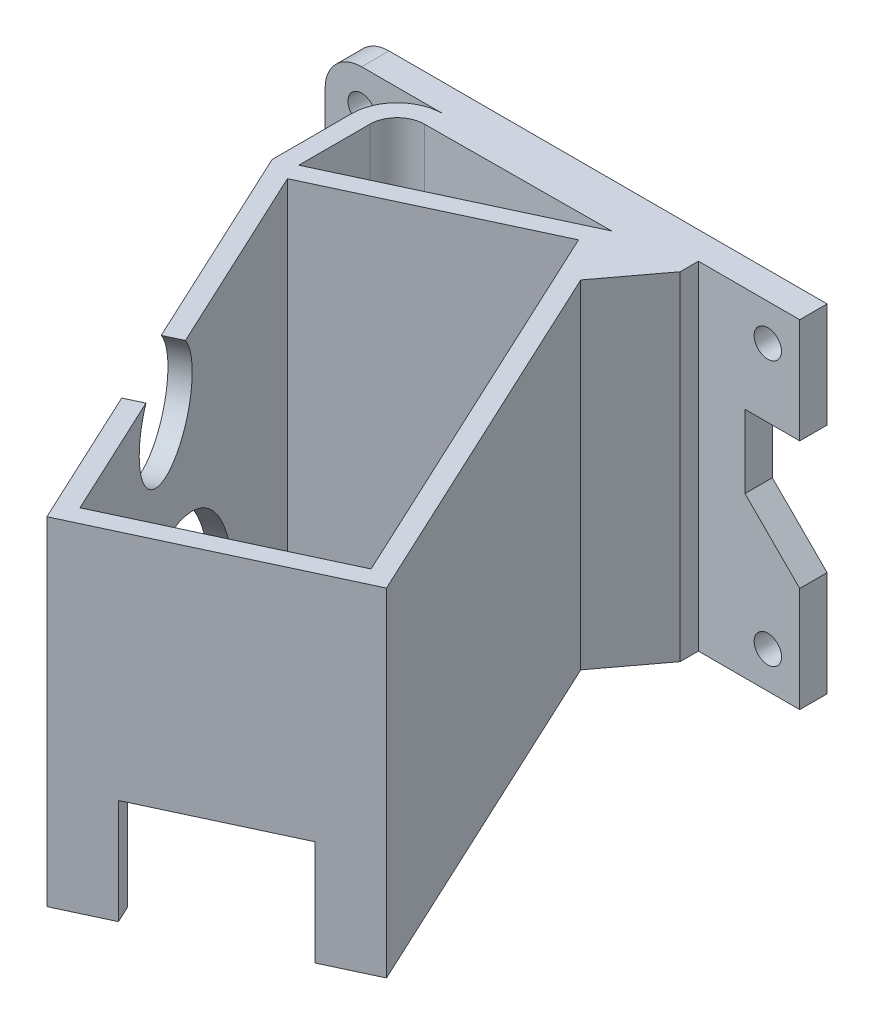
SolidWorks part; units mm, degrees
ref_plane "Alzado" through (0, 0, 0) normal (0, 0, 1) x (1, 0, 0)
ref_plane "Planta" through (0, 0, 0) normal (0, 1, 0) x (1, 0, 0)
ref_plane "Vista lateral" through (0, 0, 0) normal (1, 0, 0) x (0, 0, -1)
sketch "Croquis1" plane through (0, 0, 0) normal (0, 0, 1) x (1, 0, 0)
  line L0 (-56.1973, 4.9619) -> (-49.1973, 11.9619)
  line L1 (-52.1973, 33.4619) -> (-4.1973, 33.4619)
  line L2 (-56.1973, 29.4619) -> (-56.1973, 0.4619)
  line L3 (-52.4067, -3.5381) -> (-4.1973, -3.5381)
  line L4 (-4.1973, 33.4619) -> (-4.1973, -3.5381)
  line L5 (-56.1973, 24.9619) -> (-49.1973, 24.9619)
  line L6 (-56.1973, 24.9619) -> (-56.1973, 4.9619)
  line L7 (-56.1973, 4.9619) -> (-49.1973, 4.9619)
  line L8 (-4.1973, 7.9619) -> (-10.1973, 13.9619)
  line L9 (-4.1973, 21.9619) -> (-10.1973, 21.9619)
  line L10 (-4.1973, 21.9619) -> (-4.1973, 7.9619)
  line L11 (-4.1973, 7.9619) -> (-10.1973, 7.9619)
  line L13 (-49.1973, 11.9619) -> (-49.1973, 24.9619)
  line L14 (-10.1973, 13.9619) -> (-10.1973, 21.9619)
  circle A0 centre (-52.1973, 29.4619) radius 1.5
  circle A1 centre (-7.6973, 29.4619) radius 1.5
  circle A2 centre (-52.1915, 0.4619) radius 1.5
  circle A3 centre (-7.6915, 0.4619) radius 1.5
  arc A4 (-56.1973, 29.4619) -> (-52.1973, 33.4619) centre (-52.1973, 29.4619) cw
  arc A5 (-52.4067, -3.5381) -> (-56.1973, 0.4619) centre (-52.1915, 0.4619) cw
  dimension "D3" = 4
  dimension "D5" = 44.5
  dimension "D6" = 4
  dimension "D7" = 29
  dimension "D1" = 8.5
  dimension "D2" = 20
  dimension "D4" = 4
  dimension "D8" = 4
  dimension "D9" = 44.5
  dimension "D10" = 7
  dimension "D11" = 11.5
  dimension "D12" = 6
  dimension "D13" = 14
  dimension "D14" = 48
extrude "Saliente-Extruir1" add sketch "Croquis1" along normal blind 3
sketch "Croquis3" plane through (0, -3.5381, 0) normal (0, -1, 0) x (1, 0, 0)
  line L0 (-4.1973, 3) -> (-10.1973, 3) construction
  line L1 (-52.4067, 3) -> (-4.1973, 3) construction
  line L2 (-28.302, 3) -> (-15.302, 3)
  line L3 (-28.302, 3) -> (-43.302, 3)
  line L4 (-43.302, 3) -> (-43.302, 8) construction
  line L5 (-15.302, 3) -> (-15.302, 8) construction
  line L6 (-15.302, 8) -> (-10.302, 8) construction
  line L7 (-43.302, 8) -> (-48.302, 8) construction
  line L8 (-19.967, 11.2263) -> (-15.302, 5)
  line L9 (-1.3718, 51.1038) -> (-48.302, 16.7155) construction
  line L10 (-26.7485, 62.9372) -> (-1.3718, 51.1038)
  line L11 (-48.302, 16.7155) -> (-48.302, 8)
  line L12 (-48.302, 16.7155) -> (-26.7485, 62.9372)
  line L13 (-1.3718, 51.1038) -> (-19.967, 11.2263)
  line L14 (-48.302, 16.7155) -> (-22.9254, 4.8821) construction
  line L15 (-26.7485, 62.9372) -> (-22.9254, 4.8821) construction
  line L16 (-24.8369, 33.9097) -> (-14.0601, 57.0205) construction
  line L17 (-45.6441, 17.6828) -> (-25.7811, 60.2793)
  line L18 (-45.6441, 17.6828) -> (-23.8927, 7.54)
  line L19 (-25.7811, 60.2793) -> (-4.0297, 50.1365)
  line L20 (-23.8927, 7.54) -> (-4.0297, 50.1365)
  line L21 (-45.6441, 17.6828) -> (-4.0297, 50.1365) construction
  line L22 (-25.7811, 60.2793) -> (-23.8927, 7.54) construction
  line L23 (-48.302, 8) -> (-46.302, 8) construction
  line L24 (-43.302, 3) -> (-43.302, 5) construction
  line L25 (-10.302, 8) -> (-12.302, 8) construction
  line L26 (-43.302, 5) -> (-22.9254, 4.8821)
  line L27 (-46.302, 8) -> (-46.302, 15.7828)
  line L29 (-46.302, 15.7828) -> (-22.9254, 4.8821)
  line L30 (-15.302, 5) -> (-15.302, 3)
  arc A0 (-48.302, 8) -> (-43.302, 3) centre (-43.302, 8) ccw
  arc A2 (-46.302, 8) -> (-43.302, 5) centre (-43.302, 8) ccw
  dimension "D2" = 2
  dimension "D3" = 51
  dimension "D4" = 28
  dimension "D5" = 2
  dimension "D7" = 13
extrude "Saliente-Extruir2" add sketch "Croquis3" against normal up to vertex (37 mm away)
sketch "Croquis4" plane through (-46.0773, 0, 21.4862) normal (-0.9063, 0, 0.4226) x (0.4226, 0, 0.9063)
  line L0 (45.736, 14.9619) -> (45.736, 17.4619) construction
  line L1 (45.736, 33.4619) -> (45.736, -3.5381) construction
  line L2 (45.736, 17.4619) -> (6.8737, 17.4619) construction
  line L4 (24.3164, 17.4619) -> (24.3164, 1.9619) construction
  line L6 (24.3164, 17.4619) -> (24.3164, 29.4619) construction
  circle A0 centre (24.3164, 1.9619) radius 15.5
  circle A1 centre (24.3164, 29.4619) radius 6
extrude "Cortar-Extruir1" cut sketch "Croquis4" against normal up to vertex (2 mm away)
sketch "Croquis5" plane through (19.3289, 0, 41.4509) normal (0.4226, 0, 0.9063) x (0.9063, 0, -0.4226)
  line L0 (-36.8407, -3.5381) -> (-44.9407, -3.5381)
  line L1 (-22.8407, -3.5381) -> (-50.8407, -3.5381) construction
  line L2 (-44.9407, -3.5381) -> (-44.9407, 7.9619)
  line L3 (-44.9407, 7.9619) -> (-28.7407, 7.9619)
  line L4 (-28.7407, 7.9619) -> (-28.7407, -3.5381)
  line L5 (-28.7407, -3.5381) -> (-36.8407, -3.5381)
extrude "Cortar-Extruir2" cut sketch "Croquis5" against normal up to vertex (2 mm away)
